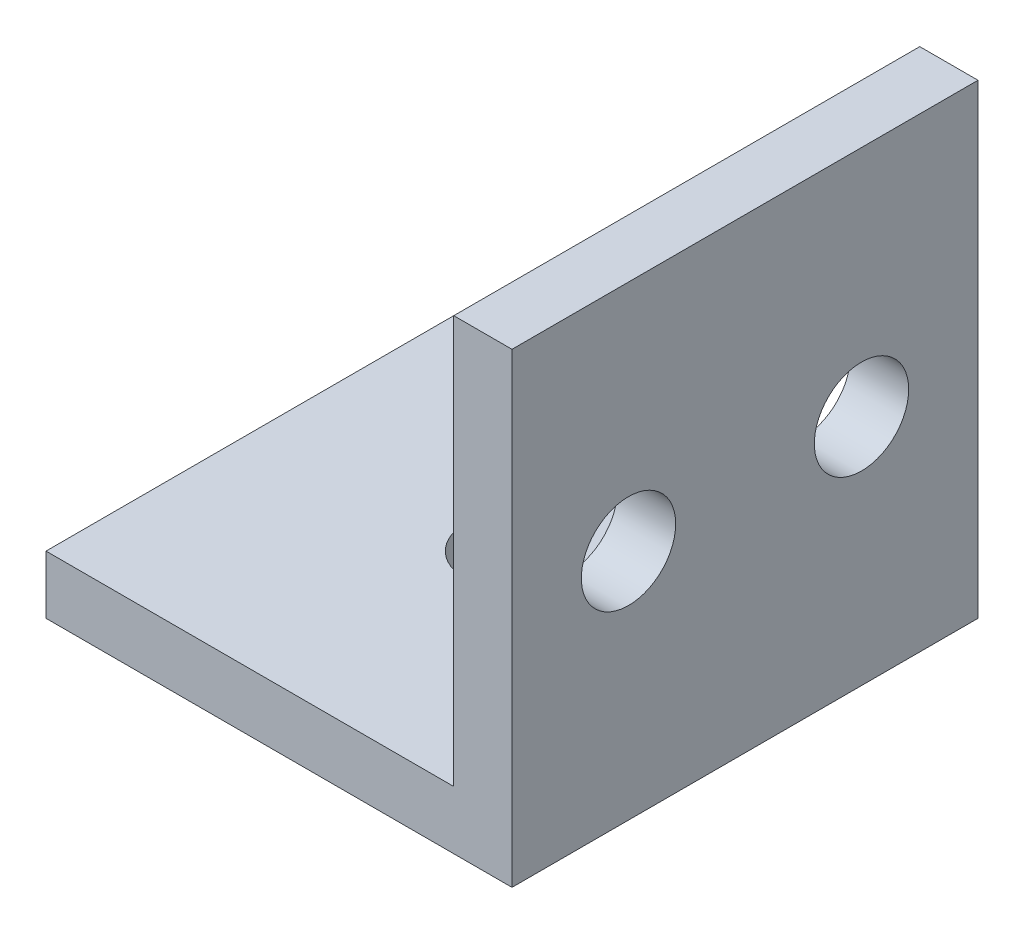
SolidWorks part; units mm, degrees
ref_plane "前视基准面" through (0, 0, 0) normal (0, 0, 1) x (1, 0, 0)
ref_plane "上视基准面" through (0, 0, 0) normal (0, 1, 0) x (1, 0, 0)
ref_plane "右视基准面" through (0, 0, 0) normal (1, 0, 0) x (0, 0, -1)
sketch "草图1" plane through (0, 0, 0) normal (0, 1, 0) x (1, 0, 0)
  line L1 (-20, 20) -> (20, 20)
  line L2 (-20, 20) -> (-20, -20)
  line L3 (-20, -20) -> (20, -20)
  line L4 (20, 20) -> (20, -20)
  circle A0 centre (0, 0) radius 4.05
  dimension "D1" = 20
  dimension "D2" = 40
  dimension "D3" = 40
  dimension "D4" = 20
extrude "凸台-拉伸1" add sketch "草图1" along normal blind 5
sketch "草图2" plane through (0, 5, 0) normal (0, 1, 0) x (1, 0, 0)
  line L0 (20, 20) -> (-20, 20) construction
  line L2 (15, 20) -> (20, 20)
  line L3 (15, 20) -> (15, -20)
  line L4 (15, -20) -> (20, -20)
  line L5 (20, 20) -> (20, -20)
  dimension "D1" = 5
extrude "凸台-拉伸2" add sketch "草图2" along normal blind 35
sketch "草图3" plane through (20, 0, 0) normal (1, 0, 0) x (0, 0, -1)
  line L0 (-20, 40) -> (-20, 0) construction
  line L1 (-20, 0) -> (20, 0) construction
  circle A0 centre (-10, 20) radius 4.05
  circle A1 centre (10, 20) radius 4.05
  dimension "D1" = 10
  dimension "D3" = 2
  dimension "D2" = 20
extrude "切除-拉伸1" cut sketch "草图3" against normal blind 35
